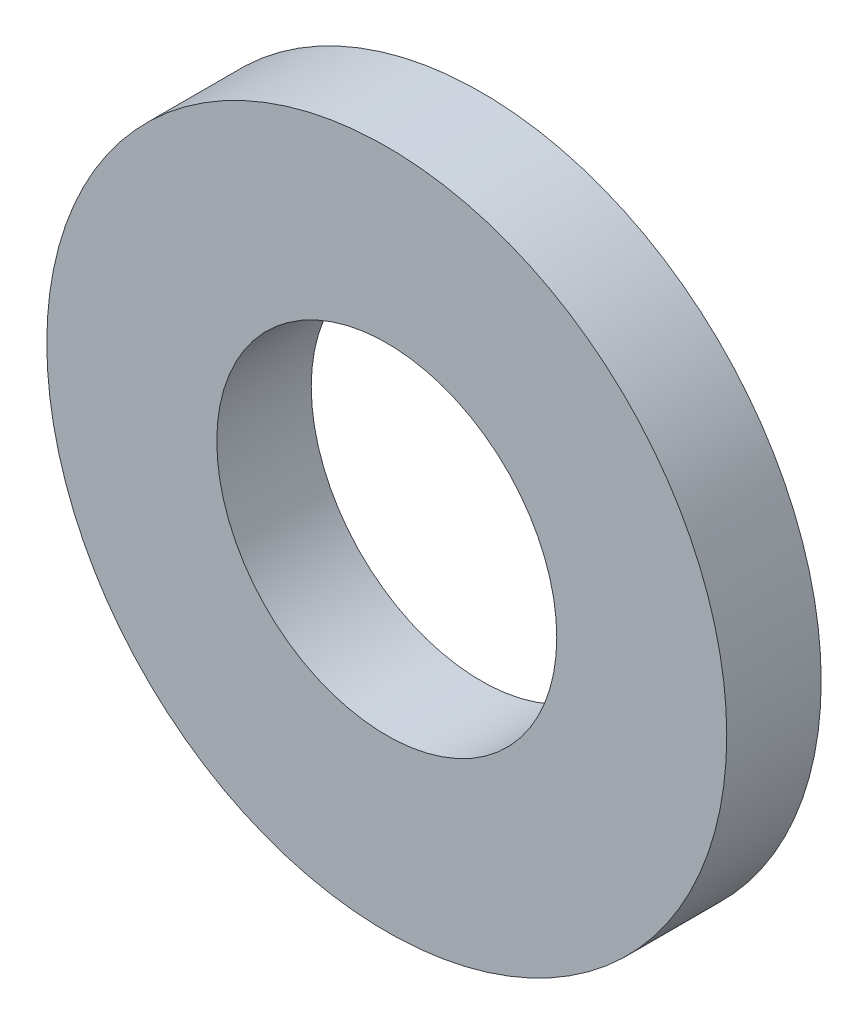
SolidWorks part; units mm, degrees
material "PLA"
ref_plane "Front Plane" through (0, 0, 0) normal (0, 0, 1) x (1, 0, 0)
ref_plane "Top Plane" through (0, 0, 0) normal (0, 1, 0) x (1, 0, 0)
ref_plane "Right Plane" through (0, 0, 0) normal (1, 0, 0) x (0, 0, -1)
sketch "Sketch1" plane through (0, 0, 0) normal (0, 0, 1) x (1, 0, 0)
  circle A0 centre (0, 0) radius 9
  circle A1 centre (0, 0) radius 4.5
  dimension "D1" = 18
  dimension "D2" = 9
extrude "Boss-Extrude1" add sketch "Sketch1" along normal mid plane 2.5
